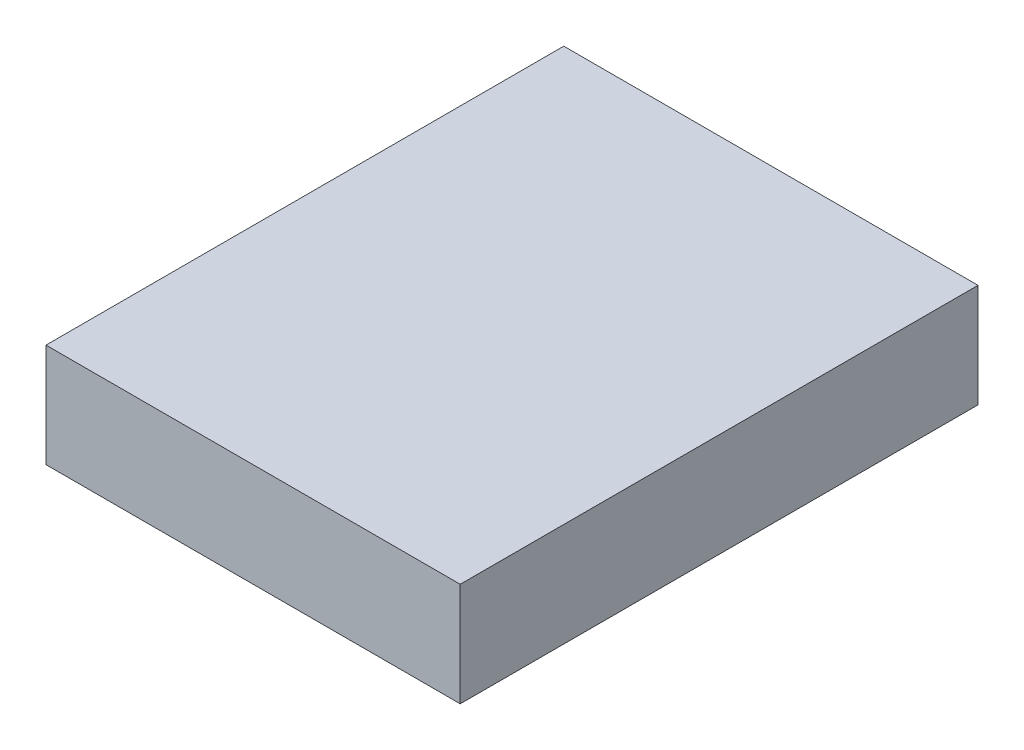
SolidWorks part; units mm, degrees
ref_plane "Front Plane" through (0, 0, 0) normal (0, 0, 1) x (1, 0, 0)
ref_plane "Top Plane" through (0, 0, 0) normal (0, 1, 0) x (1, 0, 0)
ref_plane "Right Plane" through (0, 0, 0) normal (1, 0, 0) x (0, 0, -1)
sketch "Sketch1" plane through (0, 0, 0) normal (0, 1, 0) x (1, 0, 0)
  line L1 (0, 0) -> (10.16, 0)
  line L2 (0, 0) -> (0, 12.7)
  line L3 (0, 12.7) -> (10.16, 12.7)
  line L4 (10.16, 0) -> (10.16, 12.7)
  dimension "D1" = 10.16
  dimension "D2" = 12.7
extrude "Boss-Extrude1" add sketch "Sketch1" along normal blind 2.54
